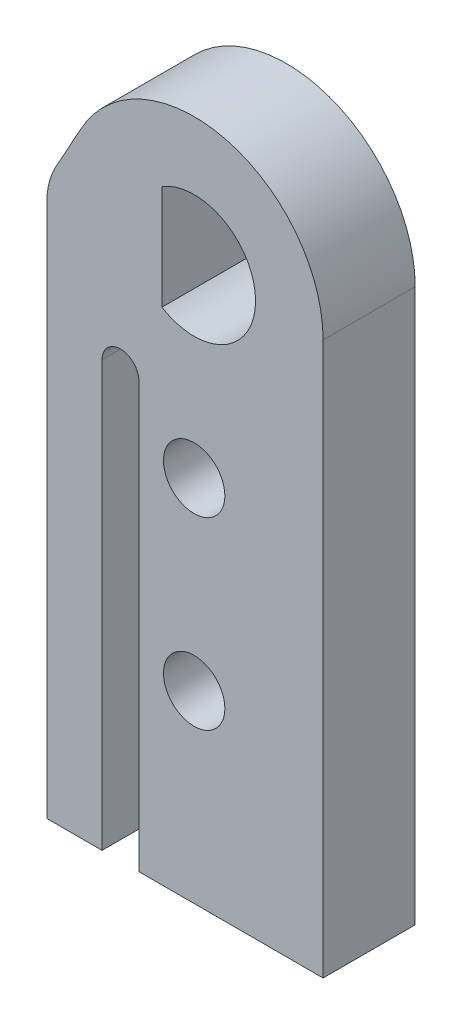
SolidWorks part; units mm, degrees
ref_plane "前视基准面" through (0, 0, 0) normal (0, 0, 1) x (1, 0, 0)
ref_plane "上视基准面" through (0, 0, 0) normal (0, 1, 0) x (1, 0, 0)
ref_plane "右视基准面" through (0, 0, 0) normal (1, 0, 0) x (0, 0, -1)
sketch "草图1" plane through (0, 0, 0) normal (0, 0, 1) x (1, 0, 0)
  line L0 (-8.8021, 25.0149) -> (-8.8021, 38.8579)
  line L1 (-10.0021, 38.8579) -> (-10.0021, 25.0149)
  line L2 (-2.8021, 25.0149) -> (-2.8021, 43.0149)
  line L6 (-11.8021, 42.3949) -> (-11.8021, 25.0149)
  line L7 (-10.7074, 44.9924) -> (-11.5019, 43.5573)
  line L8 (-8.0521, 43.0149) -> (-8.0521, 41.3127)
  line L9 (-8.0521, 43.0149) -> (-8.0521, 44.7171)
  line L10 (-11.8021, 25.0149) -> (-10.0021, 25.0149)
  line L11 (-8.8021, 25.0149) -> (-2.8021, 25.0149)
  arc A0 (-8.8021, 38.8579) -> (-10.0021, 38.8579) centre (-9.4021, 38.8579) ccw
  arc A3 (-8.0521, 41.3127) -> (-8.0521, 44.7171) centre (-7.0021, 43.0149) ccw
  arc A12 (-11.5019, 43.5573) -> (-11.8021, 42.3949) centre (-9.4021, 42.3949) ccw
  arc A13 (-2.8021, 43.0149) -> (-10.7074, 44.9924) centre (-7.0021, 43.0149) ccw
  circle A17 centre (-7.0021, 37.0149) radius 1
  circle A18 centre (-7.0021, 31.0149) radius 1
  dimension "D4" = 2
  dimension "D5" = 2
  dimension "D6" = 6
  dimension "D7" = 6
  dimension "D8" = 6
extrude "凸台-拉伸2" add sketch "草图1" along normal blind 3
